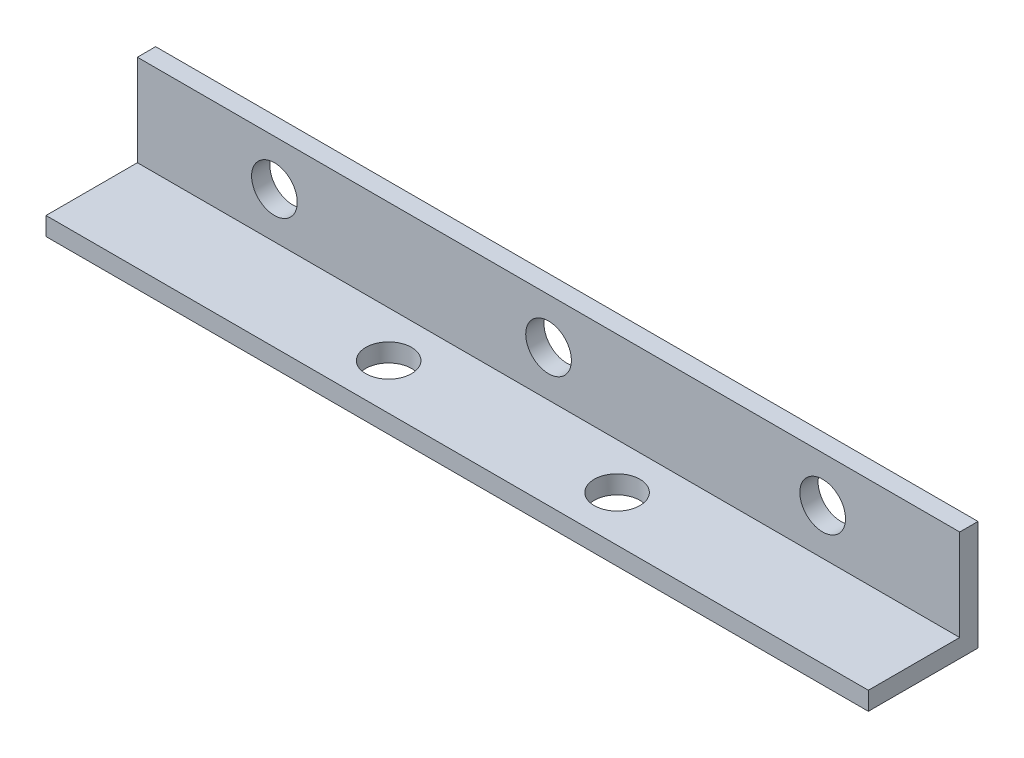
SolidWorks part; units mm, degrees
ref_plane "Front Plane" through (0, 0, 0) normal (0, 0, 1) x (1, 0, 0)
ref_plane "Top Plane" through (0, 0, 0) normal (0, 1, 0) x (1, 0, 0)
ref_plane "Right Plane" through (0, 0, 0) normal (1, 0, 0) x (0, 0, -1)
sketch "Sketch1" plane through (0, 0, 0) normal (0, 1, 0) x (1, 0, 0)
  line L1 (-61.1667, -4.5833) -> (28.8333, -4.5833)
  line L2 (-61.1667, -4.5833) -> (-61.1667, 7.4167)
  line L3 (-61.1667, 7.4167) -> (28.8333, 7.4167)
  line L4 (28.8333, -4.5833) -> (28.8333, 7.4167)
  line L5 (-61.1667, -4.5833) -> (28.8333, 7.4167) construction
  line L6 (-61.1667, 7.4167) -> (28.8333, -4.5833) construction
  point P0 (-16.1667, 1.4167)
  dimension "D1" = 12
  dimension "D2" = 90
extrude "Boss-Extrude1" add sketch "Sketch1" along normal blind 2
sketch "Sketch2" plane through (0, 2, 0) normal (0, 1, 0) x (1, 0, 0)
  line L0 (28.8333, -4.5833) -> (28.8333, 7.4167) construction
  line L1 (-61.1667, 7.4167) -> (28.8333, 7.4167)
  line L2 (-61.1667, 7.4167) -> (-61.1667, 5.4167)
  line L3 (-61.1667, 5.4167) -> (28.8333, 5.4167)
  line L4 (28.8333, 7.4167) -> (28.8333, 5.4167)
  dimension "2" = 2
extrude "Boss-Extrude2" add sketch "Sketch2" along normal blind 10
sketch "Sketch3" plane through (0, 2, 0) normal (0, 1, 0) x (1, 0, 0)
  line L1 (28.8333, -4.5833) -> (28.8333, 5.4167) construction
  line L4 (-61.1667, -4.5833) -> (28.8333, -4.5833) construction
  circle A0 centre (-28.6667, 0.4167) radius 2.5
  circle A1 centre (-3.6667, 0.4167) radius 2.5
  dimension "D1" = 5
  dimension "D2" = 5
  dimension "D3" = 25
  dimension "D4" = 32.5
  dimension "D5" = 5
  dimension "D6" = 5
extrude "Cut-Extrude1" cut sketch "Sketch3" against normal through all both and the other way through all
sketch "Sketch4" plane through (0, 0, -7.4167) normal (0, 0, -1) x (-1, 0, 0)
  line L0 (61.1667, 12) -> (61.1667, 0) construction
  line L1 (-28.8333, 12) -> (-28.8333, 0) construction
  line L2 (6.6, 0) -> (-6.6, 0) construction
  circle A0 centre (-13.8333, 7) radius 2.5
  circle A1 centre (16.1667, 7) radius 2.5
  circle A2 centre (46.1667, 7) radius 2.5
  dimension "D4" = 5
  dimension "D1" = 45
  dimension "D2" = 15
  dimension "D3" = 15
  dimension "7" = 7
  dimension "D6" = 7
  dimension "D7" = 7
extrude "Cut-Extrude2" cut sketch "Sketch4" against normal through all both and the other way through all
